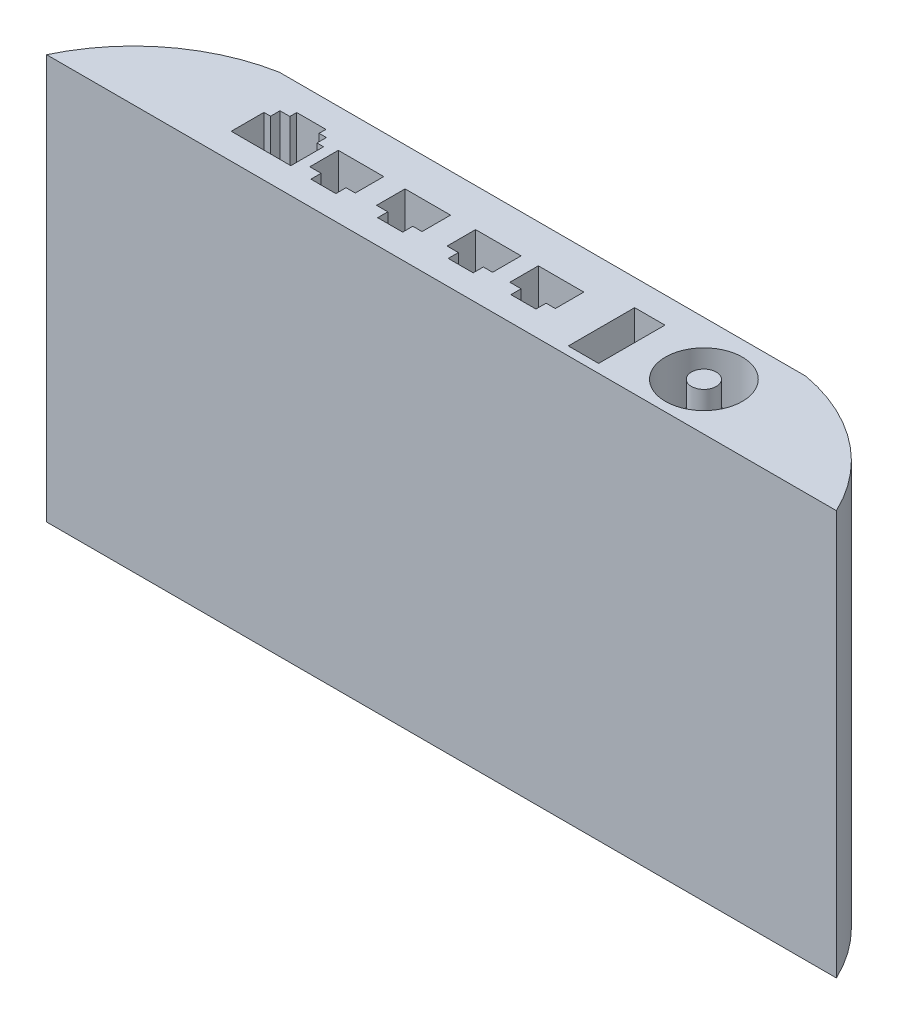
SolidWorks part; units mm, degrees
ref_plane "Front Plane" through (0, 0, 0) normal (0, 0, 1) x (1, 0, 0)
ref_plane "Top Plane" through (0, 0, 0) normal (0, 1, 0) x (1, 0, 0)
ref_plane "Right Plane" through (0, 0, 0) normal (1, 0, 0) x (0, 0, -1)
sketch "Sketch1" plane through (0, 0, 0) normal (0, 1, 0) x (1, 0, 0)
  line L0 (199.2478, -25) -> (-191.0271, -25)
  line L5 (-125.9683, 25) -> (134.1891, 25)
  line L6 (-0.6602, 0) -> (-388.6737, 0) construction
  line L7 (-109.6845, -63.5146) -> (117.9052, -63.5146) construction
  arc A0 (199.2478, -25) -> (134.1891, 25) centre (117.9052, -63.5146) ccw
  arc A1 (-191.0271, -25) -> (-125.9683, 25) centre (-109.6845, -63.5146) cw
  dimension "D1" = 50
  dimension "D2" = 90
extrude "Boss-Extrude1" add sketch "Sketch1" along normal blind 200
sketch "Sketch2" plane through (0, 200, 0) normal (0, 1, 0) x (1, 0, 0)
  line L0 (-72.4603, -7.9463) -> (-78.0259, -7.9463)
  line L1 (-55.5504, 6.1394) -> (-78.0259, 6.1394)
  line L2 (-55.5504, 6.1394) -> (-55.5504, -7.9463)
  line L3 (-55.5504, -7.9463) -> (-60.1078, -7.9463)
  line L4 (-78.0259, 6.1394) -> (-78.0259, -7.9463)
  line L6 (-60.1078, -7.9463) -> (-60.1078, -12.9707)
  line L7 (-60.1078, -12.9707) -> (-72.4603, -12.9707)
  line L8 (-72.4603, -7.9463) -> (-72.4603, -12.9707)
  line L9 (-39.4683, -7.9463) -> (-45.0338, -7.9463)
  line L10 (-22.5584, 6.1394) -> (-45.0338, 6.1394)
  line L11 (-22.5584, 6.1394) -> (-22.5584, -7.9463)
  line L12 (-22.5584, -7.9463) -> (-27.1157, -7.9463)
  line L13 (-45.0338, 6.1394) -> (-45.0338, -7.9463)
  line L14 (-27.1157, -7.9463) -> (-27.1157, -12.9707)
  line L15 (-27.1157, -12.9707) -> (-39.4683, -12.9707)
  line L16 (-39.4683, -7.9463) -> (-39.4683, -12.9707)
  line L17 (-4.6134, -7.9463) -> (-10.1789, -7.9463)
  line L18 (12.2966, 6.1394) -> (-10.1789, 6.1394)
  line L19 (12.2966, 6.1394) -> (12.2966, -7.9463)
  line L20 (12.2966, -7.9463) -> (7.7392, -7.9463)
  line L21 (-10.1789, 6.1394) -> (-10.1789, -7.9463)
  line L22 (7.7392, -7.9463) -> (7.7392, -12.9707)
  line L23 (7.7392, -12.9707) -> (-4.6134, -12.9707)
  line L24 (-4.6134, -7.9463) -> (-4.6134, -12.9707)
  line L25 (26.3955, -7.9463) -> (20.83, -7.9463)
  line L26 (43.3055, 6.1394) -> (20.83, 6.1394)
  line L27 (43.3055, 6.1394) -> (43.3055, -7.9463)
  line L28 (43.3055, -7.9463) -> (38.7481, -7.9463)
  line L29 (20.83, 6.1394) -> (20.83, -7.9463)
  line L30 (38.7481, -7.9463) -> (38.7481, -12.9707)
  line L31 (38.7481, -12.9707) -> (26.3955, -12.9707)
  line L32 (26.3955, -7.9463) -> (26.3955, -12.9707)
  line L33 (43.3055, 6.1394) -> (-78.0259, 6.1394) construction
  line L34 (-83.1797, -12.1637) -> (-83.1797, 4.0154)
  line L35 (-83.1797, 4.0154) -> (-86.4388, 4.0154)
  line L36 (-86.4388, 4.0154) -> (-86.4388, 8.6713)
  line L37 (-86.4388, 8.6713) -> (-90.0471, 8.6713)
  line L38 (-90.0471, 8.6713) -> (-90.0471, 12.0468)
  line L39 (-90.0471, 12.0468) -> (-104.4803, 12.0468)
  line L40 (-104.4803, 12.0468) -> (-104.4803, 8.6713)
  line L41 (-104.4803, 8.6713) -> (-109.369, 8.6713)
  line L42 (-109.369, 8.6713) -> (-109.369, 4.0154)
  line L43 (-109.369, 4.0154) -> (-112.6281, 4.0154)
  line L44 (-112.6281, 4.0154) -> (-112.6281, -12.1637)
  line L45 (-112.6281, -12.1637) -> (-83.1797, -12.1637)
  line L47 (77.4924, 12.0468) -> (62.5285, 12.0468)
  line L48 (77.4924, 12.0468) -> (77.4924, -20.7425)
  line L49 (77.4924, -20.7425) -> (62.5285, -20.7425)
  line L50 (62.5285, 12.0468) -> (62.5285, -20.7425)
  circle A0 centre (110.2704, -1.5032) radius 19.0051
  circle A1 centre (110.2704, -1.5032) radius 6.1505
  point P51 (110.2704, -1.5032)
extrude "Cut-Extrude1" cut sketch "Sketch2" against normal blind 25
